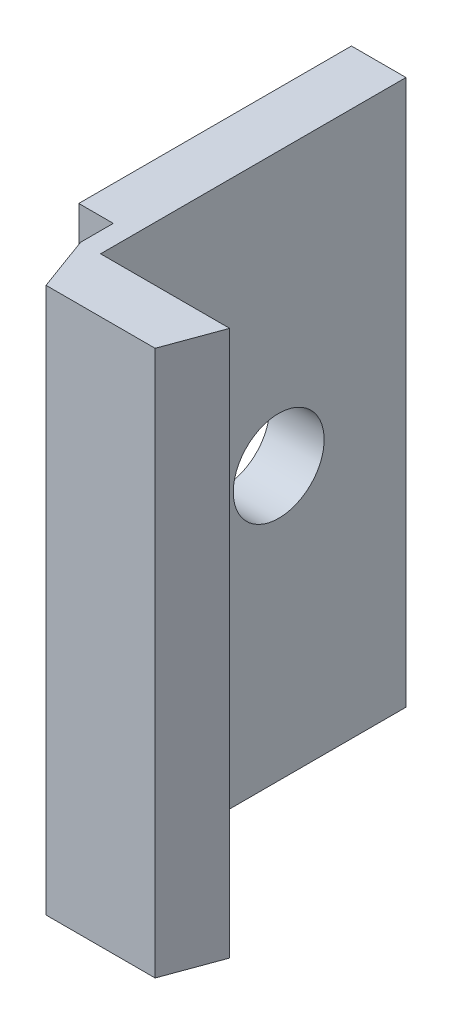
SolidWorks part; units mm, degrees
ref_plane "前视基准面" through (0, 0, 0) normal (0, 0, 1) x (1, 0, 0)
ref_plane "上视基准面" through (0, 0, 0) normal (0, 1, 0) x (1, 0, 0)
ref_plane "右视基准面" through (0, 0, 0) normal (1, 0, 0) x (0, 0, -1)
other "Configuration Table"
sketch "草图1" plane through (0, 0, 0) normal (0, 1, 0) x (1, 0, 0)
  line L0 (0, 0) -> (8.2, 0)
  line L1 (0, 0) -> (1.1, -3)
  line L2 (1.1, -3) -> (7.1, -3)
  line L3 (7.1, -3) -> (8.2, 0)
  line L4 (1.1, 0) -> (1.1, 16.8)
  line L5 (1.1, 16.8) -> (-1.9, 16.8)
  line L6 (-1.9, 16.8) -> (-1.9, 1.8)
  line L7 (4.1, 0) -> (4.1, 2.3185) construction
  line L10 (0, 0) -> (0, 1.8)
  line L11 (-1.9, 1.8) -> (0, 1.8)
  dimension "D1" = 8.2
  dimension "D2" = 3
  dimension "D3" = 6
  dimension "D4" = 3
  dimension "D5" = 19.8
  dimension "D6" = 6
  dimension "D7" = 1.8
  dimension "D8" = 1.9
extrude "凸台-拉伸1" add sketch "草图1" along normal blind 30
sketch "草图2" plane through (-1.9, 0, 0) normal (-1, 0, 0) x (0, 0, 1)
  line L0 (-16.8, 30) -> (-16.8, 0) construction
  line L1 (-1.8, 30) -> (-1.8, 0) construction
  circle A0 centre (-9.8, 15) radius 2.5
  point P4 (-16.8, 15)
  point P5 (0, 0)
  point P6 (0, 0)
  point P7 (0, 0)
  dimension "D1" = 5
  dimension "D2" = 8
extrude "切除-拉伸1" cut sketch "草图2" against normal through all both and the other way through all
